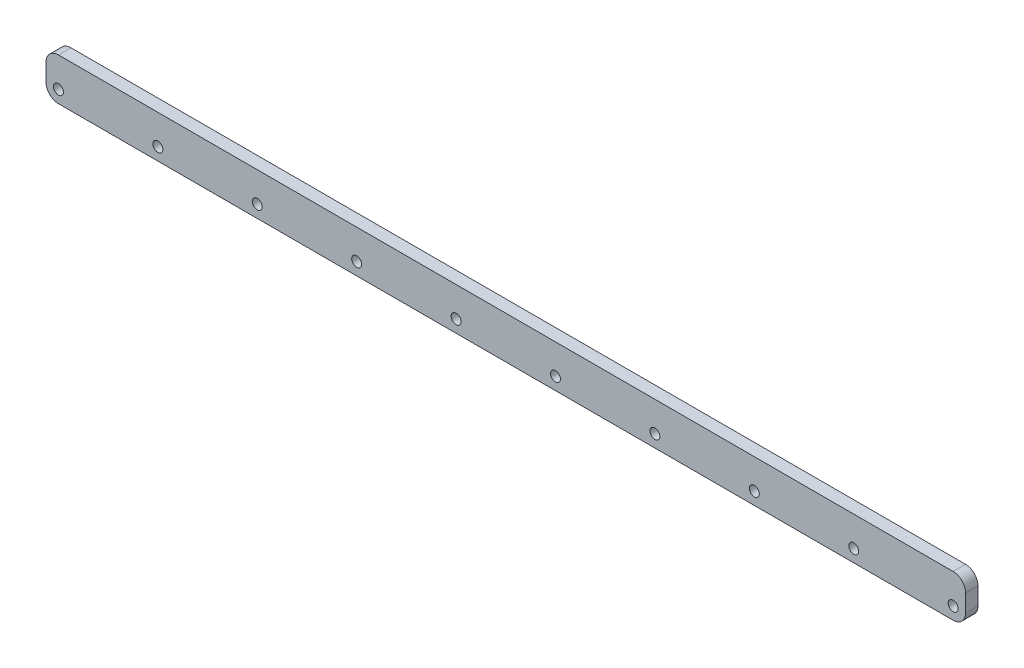
SolidWorks part; units mm, degrees
ref_plane "Plan de face" through (0, 0, 0) normal (0, 0, 1) x (1, 0, 0)
ref_plane "Plan de dessus" through (0, 0, 0) normal (0, 1, 0) x (1, 0, 0)
ref_plane "Plan de droite" through (0, 0, 0) normal (1, 0, 0) x (0, 0, -1)
sketch "Esquisse1" plane through (0, 0, 0) normal (0, 0, 1) x (1, 0, 0)
  line L0 (0, 5) -> (370, 5) construction
  line L1 (0, 0) -> (370, 0)
  line L2 (0, 0) -> (0, 17)
  line L3 (0, 17) -> (370, 17)
  line L4 (370, 0) -> (370, 17)
  circle A0 centre (5, 5) radius 2
  circle A1 centre (45, 5) radius 2
  circle A2 centre (85, 5) radius 2
  circle A3 centre (125, 5) radius 2
  circle A4 centre (165, 5) radius 2
  circle A5 centre (205, 5) radius 2
  circle A6 centre (245, 5) radius 2
  circle A7 centre (285, 5) radius 2
  circle A8 centre (325, 5) radius 2
  circle A9 centre (365, 5) radius 2
  point P9 (0, 0)
  dimension "D1" = 4
  dimension "D2" = 5
  dimension "D3" = 12
  dimension "D4" = 5
  dimension "D5" = 5
  dimension "D6" = 40
  dimension "D7" = 10
extrude "Boss.-Extru.1" add sketch "Esquisse1" along normal blind 5
fillet "Congé1" radius 5 4 edges at (370, 0, 2.5) (370, 17, 2.5) (0, 0, 2.5) (0, 17, 2.5)
